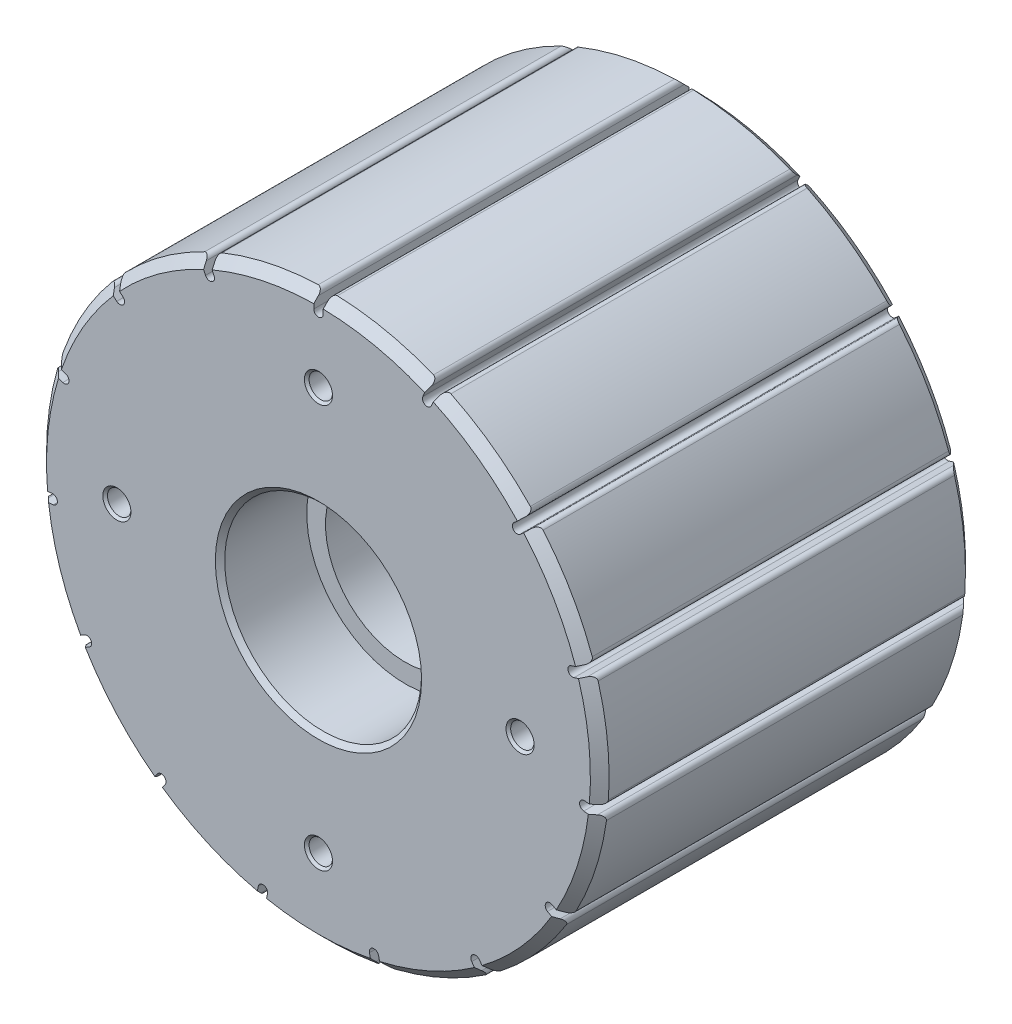
SolidWorks part; units mm, degrees
ref_plane "Front Plane" through (0, 0, 0) normal (0, 0, 1) x (1, 0, 0)
ref_plane "Top Plane" through (0, 0, 0) normal (0, 1, 0) x (1, 0, 0)
ref_plane "Right Plane" through (0, 0, 0) normal (1, 0, 0) x (0, 0, -1)
sketch "Sketch2" plane through (0, 0, 0) normal (0, 0, 1) x (1, 0, 0)
  circle A0 centre (0, 0) radius 60
  circle A1 centre (0, 0) radius 21
  dimension "D1" = 120
  dimension "D2" = 42
extrude "Boss-Extrude1" add sketch "Sketch2" along normal mid plane 80 contours A0 | A1
chamfer "Chamfer3" distance 2 angle 45 2 edges at (60, 0, 40) (60, 0, -40)
sketch "Sketch3" plane through (0, 0, 0) normal (0, 0, 1) x (1, 0, 0)
  line L0 (0, 0) -> (0, 60) construction
  line L1 (0, 60) -> (0, 57) construction
  line L2 (1, 60) -> (1, 57)
  line L3 (-1, 60) -> (-1, 57)
  circle A2 centre (0, 0) radius 60 construction
  arc A3 (1, 60) -> (-1, 60) centre (0, 60) ccw
  arc A4 (-1, 57) -> (1, 57) centre (0, 57) ccw
  point P1 (0, 58.5)
  dimension "D2" = 1
  dimension "D1" = 3
extrude "Cut-Extrude1" cut sketch "Sketch3" against normal through all both and the other way through all
fillet "Fillet1" radius 1 2 edges at (-1, 59.9917, 0) (1, 59.9917, 0)
pattern_circular "CirPattern1" count 15 over 360 about axis through (0, 0, 0) along (0, 0, 1) of "Fillet1", "Cut-Extrude1"
sketch "Sketch4" plane through (0, 0, 0) normal (0, 0, 1) x (1, 0, 0)
  circle A1 centre (0, 0) radius 17
  circle A2 centre (0, 0) radius 21 construction
  circle A3 centre (0, 0) radius 21
  dimension "D1" = 34
extrude "Boss-Extrude2" add sketch "Sketch4" along normal mid plane 43
sketch "Sketch6" plane through (0, 0, 0) normal (1, 0, 0) x (0, 0, -1)
  line L0 (0, 0) -> (56.4596, 0) construction
  line L1 (35.25, 0) -> (33.4, 0)
  line L2 (35.25, 0) -> (35.25, -23.75)
  line L3 (35.25, -23.75) -> (33.4, -23.75)
  line L4 (33.4, 0) -> (33.4, -23.75)
  line L6 (21.5, -17) -> (21.5, 17) construction
  dimension "D1" = 1.85
  dimension "D2" = 47.5
  dimension "D3" = 13.75
revolve "Cut-Revolve1" cut sketch "Sketch6" angle 360 about L0
chamfer "Chamfer2" distance 1 angle 45 2 edges at (21, 0, -40) (21, 0, 40)
sketch "Sketch8" plane through (0, 0, 40) normal (0, 0, 1) x (1, 0, 0)
  circle A0 centre (0, 0) radius 43 construction
  circle A1 centre (0, 43) radius 2.5
  dimension "D1" = 86
  dimension "D2" = 5
extrude "Cut-Extrude2" cut sketch "Sketch8" along a picked direction on the side against the normal blind 25
sketch "Sketch9" plane through (0, 0, 15) normal (0, 0, 1) x (1, 0, 0)
  circle A0 centre (0, 43) radius 2.5 construction
  circle A1 centre (0, 43) radius 2.5
extrude "Cut-Extrude3" cut sketch "Sketch9" against normal blind 3 draft 65
chamfer "Chamfer1" distance 0.5 angle 45 1 edges at (2.5, 43, 40)
pattern_circular "CirPattern2" count 4 over 360 about axis through (0, 0, 0) along (0, 0, 1) of "Cut-Extrude2", "Cut-Extrude3", "Chamfer1"
equation "\"d_ext_rouleau\"= 120"
equation "\"D1@Sketch2\"=\"d_ext_rouleau\""
equation "\"epaisseur_rouleau\"=80"
equation "\"D1@Boss-Extrude1\"=\"epaisseur_rouleau\""
equation "\"alesage-rouleau\"= 52"
equation "\"D2@Sketch2\"=\"d_ext_roulement_rouleau\""
equation "\"jeu_dent_rouleau\"= 2"
equation "\"profondeur_dent_rouleau\"=4"
equation "\"D2@Sketch3\"=\"jeu_dent_rouleau\"/2"
equation "\"D1@Sketch3\"=\"profondeur_dent_rouleau\"-\"D2@Sketch3\""
equation "\"D1@Fillet1\"=\"jeu_dent_rouleau\"/2"
equation "\"n_dent_roueau\"= 15"
equation "\"D1@CirPattern1\"=\"n_dent_roueau\""
equation "\"D1@Sketch4\"=\"d_ext_roulement_rouleau\"-8"
equation "\"B_roulement_rouleau\"= 12"
equation "\"D1@Boss-Extrude2\"=\"epaisseur_rouleau\" - ((\"B_roulement_rouleau\" + 6.5)*2)"
equation "\"F_anneau_alesage_rouleau\"=1.85"
equation "\"D1@Sketch6\"=\"F_anneau_alesage_rouleau\""
equation "\"G_anneau_alesage_rouleau\"=47.5"
equation "\"D2@Sketch6\"=\"G_anneau_alesage_rouleau\""
equation "\"K_anneau_alesage_rouleau\"=3.75"
equation "\"d_vis_flasque_rouleau\"=5"
equation "\"D2@Sketch8\"=\"d_vis_flasque_rouleau\""
equation "\"h_matrice\"= 15"
equation "\"d_matrice\"= 250"
equation "\"d_granulat\"= 8"
equation "\"zone_vide_matrice\" = 70"
equation "\"d_alesage_matrice\"=50"
equation "\"a_clavette_alesage_matrice\"=16"
equation "\"entrax_vis_rouleau\"=86"
equation "\"D1@Sketch8\"=\"entrax_vis_rouleau\""
equation "\"l-x_vis_flasque_rouleau\"=4"
equation "\"d_ext_roulement_rouleau\"= 42"
equation "\"d_int_roulement_rouleau\"= 20"
equation "\"D3@Sketch6\"=\"B_roulement_rouleau\"+1.75"
